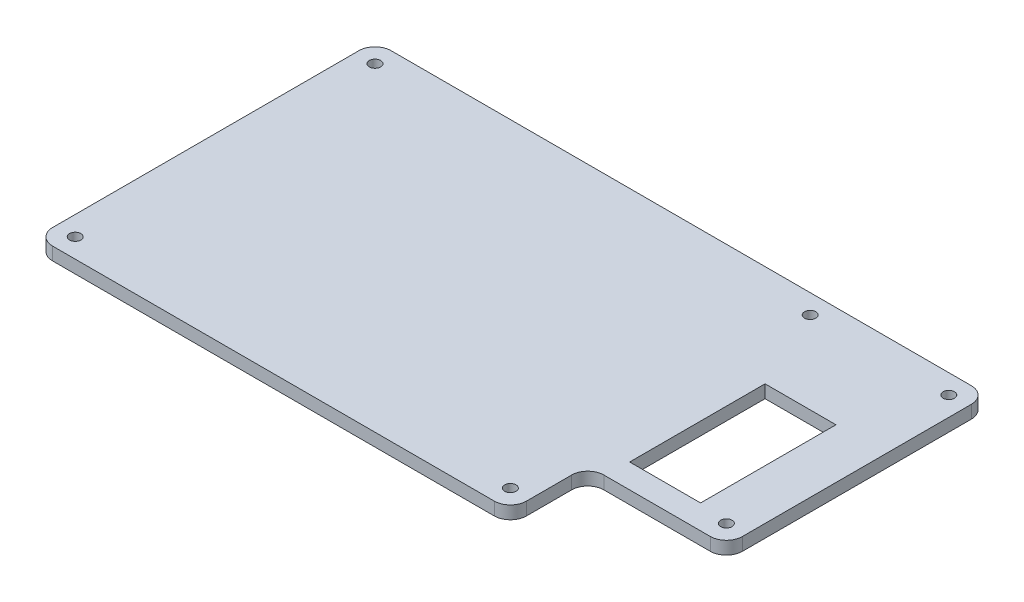
SolidWorks part; units mm, degrees
ref_plane "前视基准面" through (0, 0, 0) normal (0, 0, 1) x (1, 0, 0)
ref_plane "上视基准面" through (0, 0, 0) normal (0, 1, 0) x (1, 0, 0)
ref_plane "右视基准面" through (0, 0, 0) normal (1, 0, 0) x (0, 0, -1)
sketch "草图1" plane through (0, 0, 0) normal (0, 1, 0) x (1, 0, 0)
  line L0 (0, 0) -> (95, 0) construction
  line L1 (-95, 52.5) -> (95, 52.5)
  line L2 (-95, 52.5) -> (-95, -52.5)
  line L3 (-95, -52.5) -> (52, -52.5)
  line L4 (95, 52.5) -> (95, -28.5)
  line L5 (-95, 52.5) -> (95, -52.5) construction
  line L6 (-95, -52.5) -> (95, 52.5) construction
  line L8 (57.5, -21) -> (79.5, -21)
  line L9 (57.5, -21) -> (57.5, 21)
  line L10 (57.5, 21) -> (79.5, 21)
  line L11 (79.5, -21) -> (79.5, 21)
  line L12 (57.5, -21) -> (79.5, 21) construction
  line L13 (57.5, 21) -> (79.5, -21) construction
  line L14 (52, -28.5) -> (95, -28.5)
  line L15 (52, -52.5) -> (52, -28.5)
  circle A0 centre (-89, -46.5) radius 1.75
  circle A1 centre (46, -46.5) radius 1.75
  circle A2 centre (46, 46.5) radius 1.75
  circle A3 centre (-89, 46.5) radius 1.75
  circle A4 centre (89, 46.5) radius 1.75
  circle A5 centre (89, -22.5) radius 1.75
  point P0 (0, 0)
  point P10 (68.5, 0)
  dimension "D3" = 6
  dimension "D4" = 6
  dimension "D5" = 3.5
  dimension "D8" = 135
  dimension "D1" = 105
  dimension "D2" = 190
  dimension "D9" = 22
  dimension "D10" = 42
  dimension "D11" = 152.5
  dimension "D12" = 2
  dimension "D13" = 2
  dimension "D14" = 6
  dimension "D15" = 81
  dimension "D16" = 43
  dimension "D6" = 2
  dimension "D7" = 2
extrude "凸台-拉伸1" add sketch "草图1" along normal blind 4
fillet "圆角1" radius 5 6 edges at (-95, 2, -52.5) (95, 2, -52.5) (-95, 2, 52.5) (95, 2, 28.5) (52, 2, 52.5) (52, 2, 28.5)
